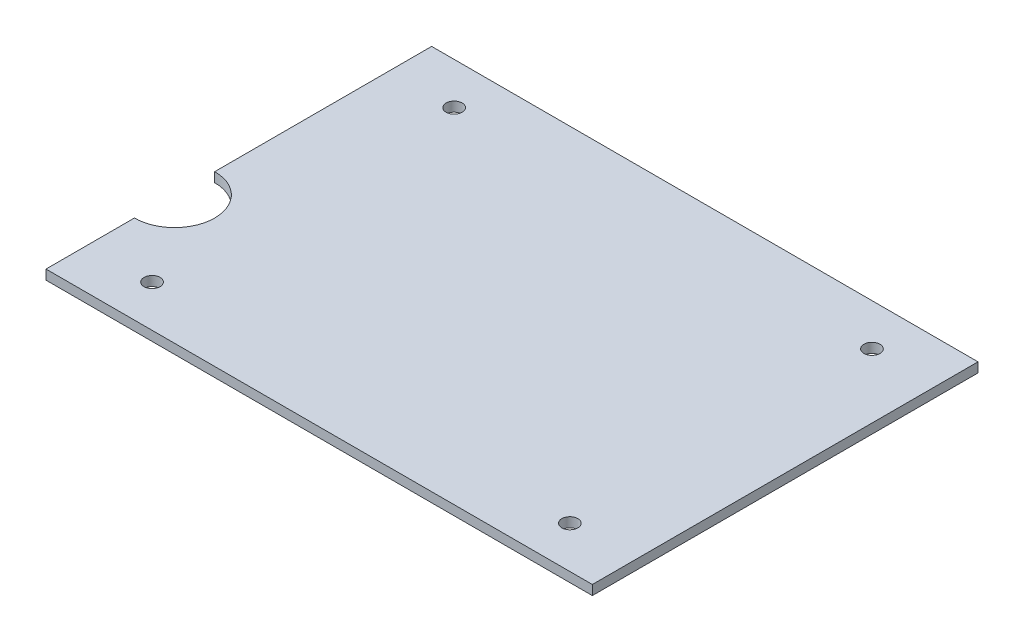
SolidWorks part; units mm, degrees
ref_plane "Front Plane" through (0, 0, 0) normal (0, 0, 1) x (1, 0, 0)
ref_plane "Top Plane" through (0, 0, 0) normal (0, 1, 0) x (1, 0, 0)
ref_plane "Right Plane" through (0, 0, 0) normal (1, 0, 0) x (0, 0, -1)
sketch "Sketch1" plane through (0, 0, 0) normal (0, 1, 0) x (1, 0, 0)
  line L0 (0, 87.771) -> (0, -83.8225) construction
  line L1 (-85, -60) -> (85, -60)
  line L2 (-85, -60) -> (-85, 60)
  line L3 (-85, 60) -> (85, 60)
  line L4 (85, -60) -> (85, 60)
  line L5 (-85, -60) -> (85, 60) construction
  line L6 (-85, 60) -> (85, -60) construction
  line L7 (-98.7216, 0) -> (151.9868, 0) construction
  circle A2 centre (-65, 47) radius 2.5
  circle A4 centre (-65, -47) radius 2.5
  circle A5 centre (65, -47) radius 2.5
  circle A6 centre (65, 47) radius 2.5
  point P0 (0, 0)
  dimension "D3" = 5
  dimension "D4" = 13
  dimension "D5" = 20
  dimension "D1" = 170
  dimension "D2" = 120
extrude "Boss-Extrude1" add sketch "Sketch1" along normal blind 3
sketch "Sketch2" plane through (0, 3, 0) normal (0, 1, 0) x (1, 0, 0)
  line L0 (-85, 60) -> (-85, -60) construction
  line L2 (85, -60) -> (-178.5, -60) construction
  circle A0 centre (-85, -20) radius 12.5
  dimension "D1" = 40
  dimension "D2" = 25
extrude "Cut-Extrude1" cut sketch "Sketch2" against normal up to next
